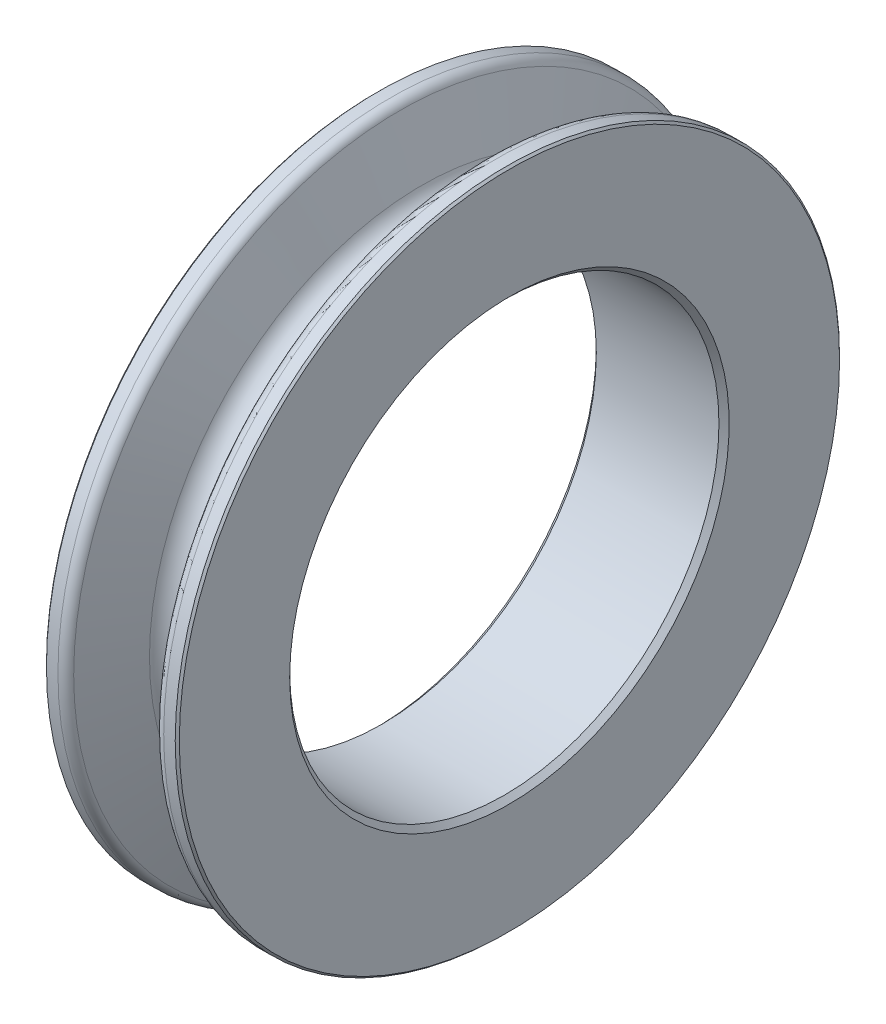
SolidWorks part; units mm, degrees
material "AISI 1020"
ref_plane "Plano frontal" through (0, 0, 0) normal (0, 0, 1) x (1, 0, 0)
ref_plane "Plano superior" through (0, 0, 0) normal (0, 1, 0) x (1, 0, 0)
ref_plane "Plano direito" through (0, 0, 0) normal (1, 0, 0) x (0, 0, -1)
sketch "Esboço1" plane through (0, 0, 0) normal (0, 0, 1) x (1, 0, 0)
  line L0 (0, 0) -> (24.7833, 0) construction
  line L1 (0, 0) -> (0, 27.5) construction
  line L2 (4.5065, 32.5) -> (2.0787, 26.639)
  line L3 (4.5065, 32.5) -> (6.5, 32.5)
  line L4 (6.5, 32.5) -> (6.5, 21)
  line L5 (6.5, 21) -> (-6.5, 21)
  line L6 (-6.5, 32.5) -> (-6.5, 21)
  line L7 (-4.5065, 32.5) -> (-6.5, 32.5)
  line L8 (-4.5065, 32.5) -> (-2.0787, 26.639)
  arc A0 (-2.0787, 26.639) -> (2.0787, 26.639) centre (0, 27.5) ccw
  point P11 (0, 21)
  dimension "D1" = 4.5
  dimension "D2" = 55
  dimension "D3" = 65
  dimension "D4" = 45
  dimension "D5" = 13
  dimension "D6" = 42
revolve "Revolução1" add sketch "Esboço1" angle 360 about L0
fillet "Filete2" radius 1 2 edges at (4.5065, 0, 32.5) (-4.5065, 0, 32.5)
chamfer "Chanfro2" distance 0.2 angle 45 2 edges at (-6.5, 0, 32.5) (6.5, 0, 32.5)
chamfer "Chanfro3" distance 0.5 angle 45 2 edges at (-6.5, 0, 21) (6.5, 0, 21)
